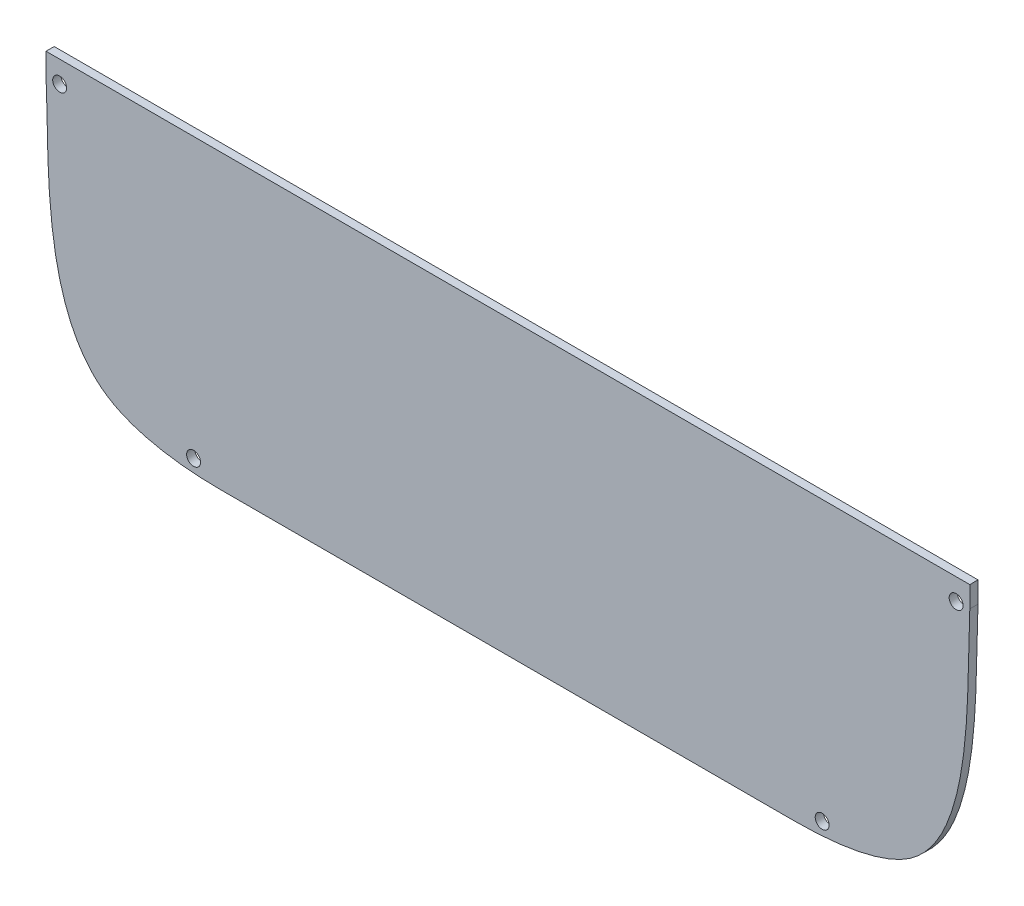
SolidWorks part; units mm, degrees
ref_plane "Front Plane" through (0, 0, 0) normal (0, 0, 1) x (1, 0, 0)
ref_plane "Top Plane" through (0, 0, 0) normal (0, 1, 0) x (1, 0, 0)
ref_plane "Right Plane" through (0, 0, 0) normal (1, 0, 0) x (0, 0, -1)
sketch "Sketch1" plane through (0, 0, 0) normal (0, 0, 1) x (1, 0, 0)
  line L12 (-105, -54) -> (100, -54)
  line L16 (159.0083, 53) -> (-169.0083, 53)
  line L17 (-169.0083, 53) -> (-169.0083, 45.3145)
  line L24 (169.0083, 45.3145) -> (169.0083, 53)
  line L25 (169.0083, 53) -> (159.0083, 53)
  line L29 (100, -54) -> (105, -54)
  circle A1 centre (-164.0083, 45.0945) radius 2.55
  circle A3 centre (-115, -49) radius 2.55
  circle A5 centre (164.0083, 45.0945) radius 2.55
  circle A7 centre (115, -49) radius 2.55
  spline S4 degree 3 poles (-169.0083, 45.3145) (-168.9751, 44.684) (-168.9167, 43.4366) (-168.8179, 40.8276) (-168.7247, 37.4372) (-168.6376, 33.1601) (-168.5265, 27.2236) (-168.3443, 19.4318) (-167.893, 9.7356) (-167.0504, -0.0449) (-165.2066, -12.8358) (-161.9916, -24.6824) (-157.0029, -34.4852) (-153.1088, -39.5883) (-149.464, -43.0153) (-146.4573, -45.2406) (-143.0464, -47.178) (-137.9779, -49.4157) (-130.8869, -51.5402) (-123.3403, -52.8496) (-117.3689, -53.496) (-113.0026, -53.8066) (-109.5333, -53.9429) (-106.8814, -53.9925) (-105.6337, -54) (-105, -54) knots 0 0 0 0 0.015625 0.03125 0.0625 0.09375 0.125 0.1875 0.25 0.3125 0.375 0.5 0.5625 0.625 0.65625 0.6875 0.71875 0.75 0.8125 0.875 0.90625 0.9375 0.96875 0.984375 1 1 1 1
  spline S8 degree 3 poles (105, -54) (105.6337, -54) (106.8814, -53.9925) (109.5333, -53.9429) (113.0026, -53.8066) (117.3689, -53.496) (123.3403, -52.8496) (130.8869, -51.5402) (137.9779, -49.4157) (143.0464, -47.178) (146.4573, -45.2406) (149.464, -43.0153) (153.1088, -39.5883) (157.0029, -34.4852) (161.9916, -24.6824) (165.2066, -12.8358) (167.0504, -0.0449) (167.893, 9.7356) (168.3443, 19.4318) (168.5265, 27.2236) (168.6376, 33.1601) (168.7247, 37.4372) (168.8179, 40.8276) (168.9167, 43.4366) (168.9751, 44.684) (169.0083, 45.3145) knots 0 0 0 0 0.015625 0.03125 0.0625 0.09375 0.125 0.1875 0.25 0.28125 0.3125 0.34375 0.375 0.4375 0.5 0.625 0.6875 0.75 0.8125 0.875 0.90625 0.9375 0.96875 0.984375 1 1 1 1
extrude "Boss-Extrude1" add sketch "Sketch1" along normal blind 3
